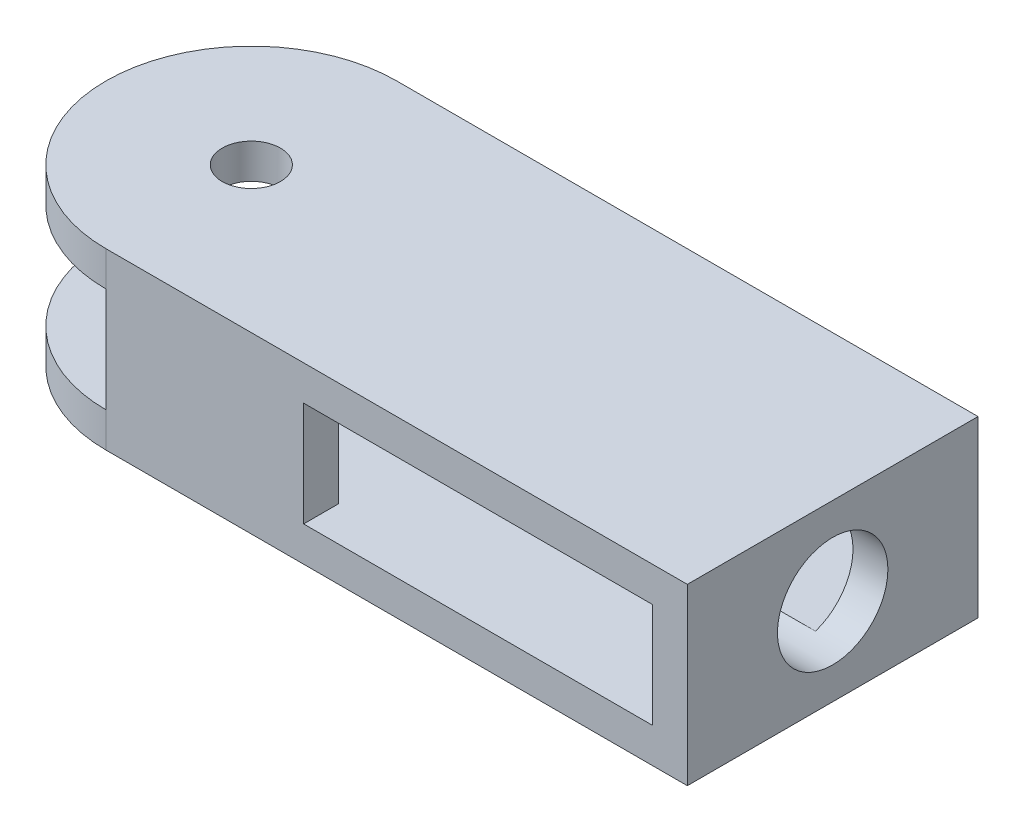
SolidWorks part; units mm, degrees
material "Acrylic (Medium-high impact)"
ref_plane "Front Plane" through (0, 0, 0) normal (0, 0, 1) x (1, 0, 0)
ref_plane "Top Plane" through (0, 0, 0) normal (0, 1, 0) x (1, 0, 0)
ref_plane "Right Plane" through (0, 0, 0) normal (1, 0, 0) x (0, 0, -1)
sketch "Sketch1" plane through (0, 0, 0) normal (0, 1, 0) x (1, 0, 0)
  line L1 (-50, 25) -> (50, 25)
  line L3 (-50, -25) -> (50, -25)
  line L4 (50, 25) -> (50, -25)
  line L5 (-50, 25) -> (50, -25) construction
  line L6 (-50, -25) -> (50, 25) construction
  arc A0 (-50, 25) -> (-50, -25) centre (-50, 0) ccw
  circle A1 centre (-50, 0) radius 5
  point P0 (0, 0)
  dimension "D3" = 10
  dimension "D1" = 100
  dimension "D2" = 50
extrude "Boss-Extrude1" add sketch "Sketch1" along normal mid plane 30
sketch "Sketch5" plane through (50, 0, 0) normal (1, 0, 0) x (0, 0, -1)
  circle A0 centre (0, 0) radius 9.5
  dimension "D1" = 19
extrude "Cut-Extrude1" cut sketch "Sketch5" against normal blind 50
sketch "Sketch6" plane through (0, 0, 0) normal (0, 0, 1) x (1, 0, 0)
  line L0 (-44, 0) -> (44, 0) construction
  line L1 (-16, 9) -> (44, 9)
  line L2 (-16, 9) -> (-16, -9)
  line L3 (-16, -9) -> (44, -9)
  line L4 (44, 9) -> (44, -9)
  line L5 (-50, 15) -> (-50, -15) construction
  line L6 (50, 15) -> (50, -15) construction
  line L7 (-50, 15) -> (50, 15) construction
  line L9 (-50, 9) -> (-75, 9)
  line L10 (-50, 9) -> (-50, -9)
  line L11 (-50, -9) -> (-75, -9)
  line L12 (-75, 9) -> (-75, -9)
  line L13 (-75, 15) -> (-75, -15) construction
  point P12 (0, 0)
  dimension "D1" = 6
  dimension "D2" = 60
  dimension "D3" = 6
extrude "Cut-Extrude2" cut sketch "Sketch6" against normal through all both and the other way through all
sketch "Sketch7" plane through (-16, 0, 0) normal (1, 0, 0) x (0, 0, -1)
  line L0 (-25, 15) -> (25, 15) construction
  line L1 (-19, 9) -> (19, 9)
  line L2 (-19, 9) -> (-19, -9)
  line L3 (-19, -9) -> (19, -9)
  line L4 (19, 9) -> (19, -9)
  line L5 (-19, 9) -> (19, -9) construction
  line L6 (-19, -9) -> (19, 9) construction
  line L7 (-25, 15) -> (-25, -15) construction
  point P0 (0, 0)
  dimension "D1" = 6
  dimension "D2" = 6
extrude "Cut-Extrude3" cut sketch "Sketch7" against normal through all
